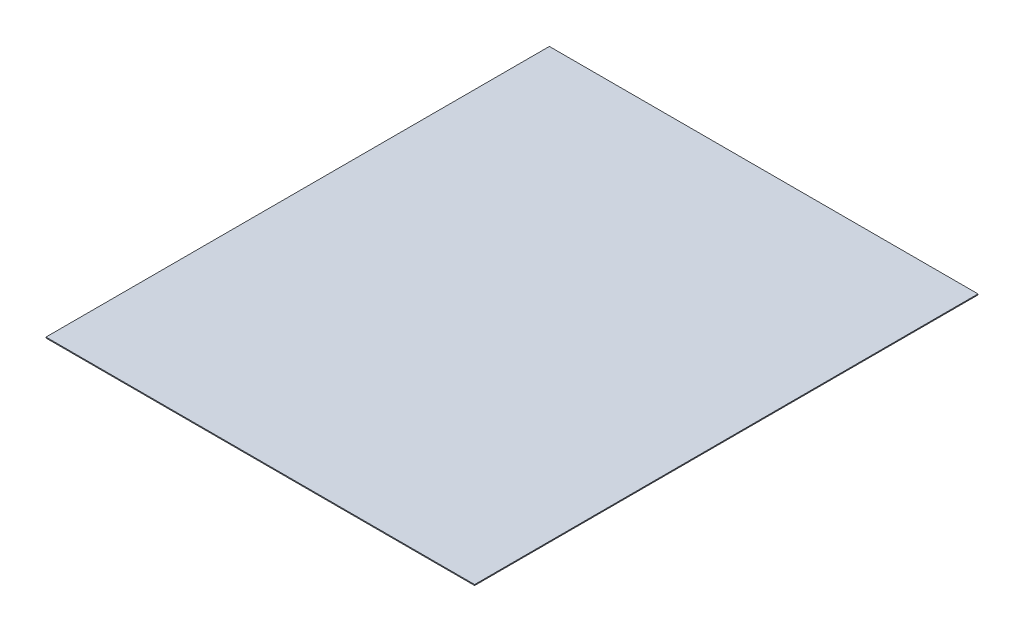
SolidWorks part; units mm, degrees
ref_plane "Front Plane" through (0, 0, 0) normal (0, 0, 1) x (1, 0, 0)
ref_plane "Top Plane" through (0, 0, 0) normal (0, 1, 0) x (1, 0, 0)
ref_plane "Right Plane" through (0, 0, 0) normal (1, 0, 0) x (0, 0, -1)
other "Configuration Table"
sketch "Sketch1" plane through (0, 0, 0) normal (0, 0, 1) x (1, 0, 0)
  line L1 (1.5, 200) -> (698.5, 200)
  line L2 (1.5, 200) -> (1.5, 201.5)
  line L3 (1.5, 201.5) -> (698.5, 201.5)
  line L4 (698.5, 200) -> (698.5, 201.5)
extrude "TOPPING_dis_alt_1" add sketch "Sketch1" against normal blind 818.5 separate body
